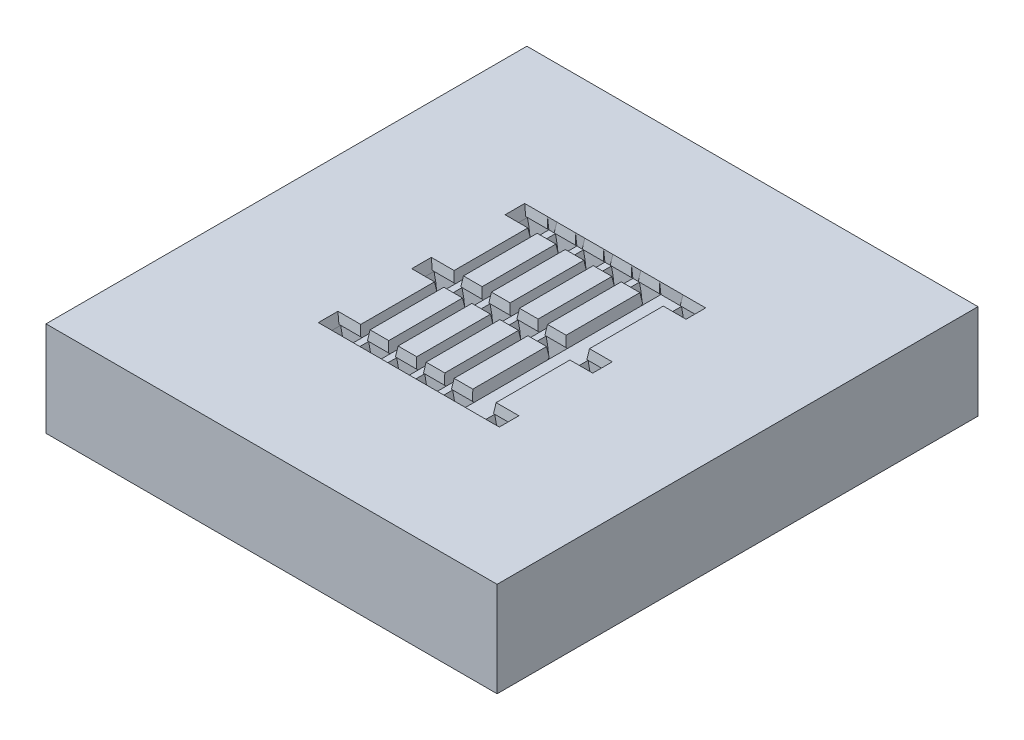
SolidWorks part; units mm, degrees
ref_plane "Front Plane" through (0, 0, 0) normal (0, 0, 1) x (1, 0, 0)
ref_plane "Top Plane" through (0, 0, 0) normal (0, 1, 0) x (1, 0, 0)
ref_plane "Right Plane" through (0, 0, 0) normal (1, 0, 0) x (0, 0, -1)
sketch "Sketch1" plane through (0, 0, 0) normal (0, 1, 0) x (1, 0, 0)
  line L0 (0, 0) -> (0, 25.75) construction
  line L1 (-24.1562, 25.75) -> (24.1562, 25.75)
  line L2 (-24.1562, 25.75) -> (-24.1562, -25.75)
  line L3 (-24.1562, -25.75) -> (24.1562, -25.75)
  line L4 (24.1562, 25.75) -> (24.1562, -25.75)
  line L5 (0, 0) -> (24.1562, 0) construction
  line L6 (24.1562, 25.75) -> (24.1562, -25.75) construction
  line L7 (-24.1562, 25.75) -> (24.1562, 25.75) construction
sketch "Sketch3" plane through (0, 0, 0) normal (1, 0, 0) x (0, 0, -1)
  line L0 (25.75, -12) -> (-25.75, -12) construction
  line L1 (25.75, 0) -> (-25.75, 0) construction
  line L2 (25.75, 0) -> (25.75, -12) construction
  line L3 (25.75, -12) -> (-25.75, -12)
  line L4 (-25.75, 0) -> (-25.75, -12) construction
  line L5 (25.75, -1.844) -> (11.05, -1.844)
  line L6 (-25.75, -1.844) -> (-25.75, -12)
  line L7 (25.75, -1.844) -> (25.75, -12)
  line L8 (1.05, -3) -> (0.9, -2.85) construction
  line L9 (0.9, -2.85) -> (1.05, -1.844) construction
  line L10 (1.05, -3) -> (1.05, -6.5) construction
  line L11 (-1.05, -3) -> (-0.9, -2.85) construction
  line L12 (-0.9, -2.85) -> (-1.05, -1.844) construction
  line L13 (-1.05, -3) -> (-1.05, -6.5) construction
  line L14 (1.05, -6.5) -> (-1.05, -6.5) construction
  line L15 (-8.95, -3) -> (-8.95, -6.5) construction
  line L16 (-8.95, -6.5) -> (-11.05, -6.5) construction
  line L17 (-11.05, -6.5) -> (-11.05, -3) construction
  line L18 (-10.9, -2.85) -> (-11.05, -1.844) construction
  line L19 (-9.1, -2.85) -> (-8.95, -1.844) construction
  line L20 (-11.05, -3) -> (-10.9, -2.85) construction
  line L21 (-8.95, -3) -> (-9.1, -2.85) construction
  line L22 (8.95, -6.5) -> (11.05, -6.5) construction
  line L23 (8.95, -3) -> (8.95, -6.5) construction
  line L24 (11.05, -6.5) -> (11.05, -3) construction
  line L25 (11.05, -3) -> (10.9, -2.85) construction
  line L26 (10.9, -2.85) -> (11.05, -1.844) construction
  line L27 (9.1, -2.85) -> (8.95, -1.844) construction
  line L28 (8.95, -3) -> (9.1, -2.85) construction
  line L29 (1.05, -3) -> (0.9, -2.85)
  line L30 (0.9, -2.85) -> (1.05, -1.844)
  line L31 (1.05, -3) -> (1.05, -6.5)
  line L32 (-1.05, -3) -> (-0.9, -2.85)
  line L33 (-0.9, -2.85) -> (-1.05, -1.844)
  line L34 (-1.05, -3) -> (-1.05, -6.5)
  line L35 (1.05, -6.5) -> (-1.05, -6.5)
  line L36 (-8.95, -3) -> (-8.95, -6.5)
  line L37 (-8.95, -6.5) -> (-11.05, -6.5)
  line L38 (-11.05, -6.5) -> (-11.05, -3)
  line L39 (-10.9, -2.85) -> (-11.05, -1.844)
  line L40 (-9.1, -2.85) -> (-8.95, -1.844)
  line L41 (-11.05, -3) -> (-10.9, -2.85)
  line L42 (-8.95, -3) -> (-9.1, -2.85)
  line L43 (8.95, -6.5) -> (11.05, -6.5)
  line L44 (8.95, -3) -> (8.95, -6.5)
  line L45 (11.05, -6.5) -> (11.05, -3)
  line L46 (11.05, -3) -> (10.9, -2.85)
  line L47 (10.9, -2.85) -> (11.05, -1.844)
  line L48 (9.1, -2.85) -> (8.95, -1.844)
  line L49 (8.95, -3) -> (9.1, -2.85)
  line L50 (8.95, -1.844) -> (1.05, -1.844)
  line L51 (-1.05, -1.844) -> (-8.95, -1.844)
  line L52 (-11.05, -1.844) -> (-25.75, -1.844)
sketch "Sketch5" plane through (0, 0, 0) normal (0, 0, 1) x (1, 0, 0)
  line L0 (-7.1005, -3) -> (-7.25, -1.844) construction
  line L1 (-7.25, -1.844) -> (-9.25, -1.844) construction
  line L2 (-9.25, -1.844) -> (-9.3995, -3) construction
  line L3 (-7.384, -6.5) -> (-9.116, -6.5) construction
  line L4 (-6.3995, -3) -> (-6.25, -1.844) construction
  line L5 (-6.25, -1.844) -> (-4.25, -1.844) construction
  line L6 (-4.25, -1.844) -> (-4.1005, -3) construction
  line L7 (-6.116, -6.5) -> (-4.384, -6.5) construction
  line L8 (-1.384, -6.5) -> (-3.116, -6.5) construction
  line L9 (-3.25, -1.844) -> (-3.3995, -3) construction
  line L10 (-1.25, -1.844) -> (-3.25, -1.844) construction
  line L11 (-1.1005, -3) -> (-1.25, -1.844) construction
  line L12 (-0.3995, -3) -> (-0.25, -1.844) construction
  line L13 (-0.116, -6.5) -> (1.616, -6.5) construction
  line L14 (1.75, -1.844) -> (1.8995, -3) construction
  line L15 (-0.25, -1.844) -> (1.75, -1.844) construction
  line L16 (4.75, -1.844) -> (2.75, -1.844) construction
  line L17 (2.75, -1.844) -> (2.6005, -3) construction
  line L18 (4.8995, -3) -> (4.75, -1.844) construction
  line L19 (4.616, -6.5) -> (2.884, -6.5) construction
  line L20 (7.384, -6.5) -> (9.116, -6.5) construction
  line L21 (7.1005, -3) -> (7.25, -1.844) construction
  line L22 (9.25, -1.844) -> (9.3995, -3) construction
  line L23 (7.25, -1.844) -> (9.25, -1.844) construction
  line L24 (-7.1005, -3) -> (-7.25, -1.844)
  line L25 (-7.25, -1.844) -> (-9.25, -1.844)
  line L26 (-9.25, -1.844) -> (-9.3995, -3)
  line L27 (-7.384, -6.5) -> (-9.116, -6.5)
  line L28 (-6.3995, -3) -> (-6.25, -1.844)
  line L29 (-6.25, -1.844) -> (-4.25, -1.844)
  line L30 (-4.25, -1.844) -> (-4.1005, -3)
  line L31 (-6.116, -6.5) -> (-4.384, -6.5)
  line L32 (-1.384, -6.5) -> (-3.116, -6.5)
  line L33 (-3.25, -1.844) -> (-3.3995, -3)
  line L34 (-1.25, -1.844) -> (-3.25, -1.844)
  line L35 (-1.1005, -3) -> (-1.25, -1.844)
  line L36 (-0.3995, -3) -> (-0.25, -1.844)
  line L37 (-0.116, -6.5) -> (1.616, -6.5)
  line L38 (1.75, -1.844) -> (1.8995, -3)
  line L39 (-0.25, -1.844) -> (1.75, -1.844)
  line L40 (4.75, -1.844) -> (2.75, -1.844)
  line L41 (2.75, -1.844) -> (2.6005, -3)
  line L42 (4.8995, -3) -> (4.75, -1.844)
  line L43 (4.616, -6.5) -> (2.884, -6.5)
  line L44 (7.384, -6.5) -> (9.116, -6.5)
  line L45 (7.1005, -3) -> (7.25, -1.844)
  line L46 (9.25, -1.844) -> (9.3995, -3)
  line L47 (7.25, -1.844) -> (9.25, -1.844)
  arc A0 (-9.116, -6.5) -> (-9.3995, -3) centre (-19.7262, -5.5981) ccw construction
  arc A1 (-7.1005, -3) -> (-7.384, -6.5) centre (3.2262, -5.5981) ccw construction
  arc A2 (-6.116, -6.5) -> (-6.3995, -3) centre (-16.7262, -5.5981) ccw construction
  arc A3 (-4.1005, -3) -> (-4.384, -6.5) centre (6.2262, -5.5981) ccw construction
  arc A4 (-3.116, -6.5) -> (-3.3995, -3) centre (-13.7262, -5.5981) ccw construction
  arc A5 (-1.1005, -3) -> (-1.384, -6.5) centre (9.2262, -5.5981) ccw construction
  arc A6 (-0.116, -6.5) -> (-0.3995, -3) centre (-10.7262, -5.5981) ccw construction
  arc A7 (1.8995, -3) -> (1.616, -6.5) centre (12.2262, -5.5981) ccw construction
  arc A8 (4.8995, -3) -> (4.616, -6.5) centre (15.2262, -5.5981) ccw construction
  arc A9 (2.884, -6.5) -> (2.6005, -3) centre (-7.7262, -5.5981) ccw construction
  arc A10 (7.384, -6.5) -> (7.1005, -3) centre (-3.2262, -5.5981) ccw construction
  arc A11 (9.3995, -3) -> (9.116, -6.5) centre (19.7262, -5.5981) ccw construction
  arc A12 (-9.116, -6.5) -> (-9.3995, -3) centre (-19.7262, -5.5981) ccw
  arc A13 (-7.1005, -3) -> (-7.384, -6.5) centre (3.2262, -5.5981) ccw
  arc A14 (-6.116, -6.5) -> (-6.3995, -3) centre (-16.7262, -5.5981) ccw
  arc A15 (-4.1005, -3) -> (-4.384, -6.5) centre (6.2262, -5.5981) ccw
  arc A16 (-3.116, -6.5) -> (-3.3995, -3) centre (-13.7262, -5.5981) ccw
  arc A17 (-1.1005, -3) -> (-1.384, -6.5) centre (9.2262, -5.5981) ccw
  arc A18 (-0.116, -6.5) -> (-0.3995, -3) centre (-10.7262, -5.5981) ccw
  arc A19 (1.8995, -3) -> (1.616, -6.5) centre (12.2262, -5.5981) ccw
  arc A20 (4.8995, -3) -> (4.616, -6.5) centre (15.2262, -5.5981) ccw
  arc A21 (2.884, -6.5) -> (2.6005, -3) centre (-7.7262, -5.5981) ccw
  arc A22 (7.384, -6.5) -> (7.1005, -3) centre (-3.2262, -5.5981) ccw
  arc A23 (9.3995, -3) -> (9.116, -6.5) centre (19.7262, -5.5981) ccw
extrude "Boss-Extrude2" add sketch "Sketch1" against normal up to vertex (12 mm away) from vertex at -1.844 starting at point (0, -1.844, 25.75)
sketch "Sketch6" plane through (0, 0, 0) normal (0, 0, 1) x (1, 0, 0)
  line L0 (-9.3995, -3) -> (-9.6904, -1.844)
  line L1 (-9.6904, -1.844) -> (9.6904, -1.844)
  line L2 (9.6904, -1.844) -> (9.3995, -3)
  line L3 (-7.25, -1.844) -> (-9.25, -1.844) construction
  line L4 (-9.116, -6.5) -> (9.116, -6.5)
  line L5 (-9.6904, -1.844) -> (-9.6904, -6.5) construction
  line L6 (-9.6904, -6.5) -> (-9.116, -6.5) construction
  line L7 (9.6904, -1.844) -> (9.6904, -6.5) construction
  line L8 (9.6904, -6.5) -> (9.116, -6.5) construction
  arc A0 (9.3995, -3) -> (9.116, -6.5) centre (19.7262, -5.5981) ccw construction
  arc A1 (-9.116, -6.5) -> (-9.3995, -3) centre (-19.7262, -5.5981) ccw construction
  arc A2 (-9.116, -6.5) -> (-9.3995, -3) centre (-19.7262, -5.5981) ccw
  arc A3 (9.3995, -3) -> (9.116, -6.5) centre (19.7262, -5.5981) ccw
sketch "Sketch7" plane through (0, 0, 0) normal (1, 0, 0) x (0, 0, -1)
  line L0 (10.9, -2.85) -> (11.05, -1.844) construction
  line L1 (-10.9, -2.85) -> (-11.05, -1.844) construction
  line L2 (-11.05, -3) -> (-10.9, -2.85) construction
  line L3 (-11.05, -6.5) -> (-11.05, -3) construction
  line L4 (-8.95, -6.5) -> (-11.05, -6.5) construction
  line L5 (-8.95, -3) -> (-8.95, -6.5) construction
  line L6 (-8.95, -3) -> (-9.1, -2.85) construction
  line L7 (-9.1, -2.85) -> (-8.95, -1.844) construction
  line L8 (-0.9, -2.85) -> (-1.05, -1.844) construction
  line L9 (-1.05, -3) -> (-0.9, -2.85) construction
  line L10 (-1.05, -3) -> (-1.05, -6.5) construction
  line L11 (1.05, -6.5) -> (-1.05, -6.5) construction
  line L12 (1.05, -3) -> (1.05, -6.5) construction
  line L13 (1.05, -3) -> (0.9, -2.85) construction
  line L14 (0.9, -2.85) -> (1.05, -1.844) construction
  line L15 (9.1, -2.85) -> (8.95, -1.844) construction
  line L16 (8.95, -3) -> (9.1, -2.85) construction
  line L17 (8.95, -3) -> (8.95, -6.5) construction
  line L18 (8.95, -6.5) -> (11.05, -6.5) construction
  line L19 (11.05, -6.5) -> (11.05, -3) construction
  line L20 (11.05, -3) -> (10.9, -2.85) construction
  line L21 (10.9, -2.85) -> (11.05, -1.844)
  line L22 (-10.9, -2.85) -> (-11.05, -1.844)
  line L23 (-11.05, -3) -> (-10.9, -2.85)
  line L24 (-11.05, -6.5) -> (-11.05, -3)
  line L25 (-8.95, -6.5) -> (-11.05, -6.5)
  line L26 (-8.95, -3) -> (-8.95, -6.5)
  line L27 (-8.95, -3) -> (-9.1, -2.85)
  line L28 (-9.1, -2.85) -> (-8.95, -1.844)
  line L29 (-0.9, -2.85) -> (-1.05, -1.844)
  line L30 (-1.05, -3) -> (-0.9, -2.85)
  line L31 (-1.05, -3) -> (-1.05, -6.5)
  line L32 (1.05, -6.5) -> (-1.05, -6.5)
  line L33 (1.05, -3) -> (1.05, -6.5)
  line L34 (1.05, -3) -> (0.9, -2.85)
  line L35 (0.9, -2.85) -> (1.05, -1.844)
  line L36 (9.1, -2.85) -> (8.95, -1.844)
  line L37 (8.95, -3) -> (9.1, -2.85)
  line L38 (8.95, -3) -> (8.95, -6.5)
  line L39 (8.95, -6.5) -> (11.05, -6.5)
  line L40 (11.05, -6.5) -> (11.05, -3)
  line L41 (11.05, -3) -> (10.9, -2.85)
  line L42 (11.05, -1.844) -> (8.95, -1.844)
  line L43 (1.05, -1.844) -> (-1.05, -1.844)
  line L44 (-8.95, -1.844) -> (-11.05, -1.844)
extrude "Cut-Extrude1" cut sketch "Sketch7" along normal up to vertex (9.6904 mm away) from vertex at -9.6904 starting at point (-9.6904, -1.844, 0)
sketch "Sketch8" plane through (0, 0, 0) normal (0, 0, 1) x (1, 0, 0)
  line L0 (-7.25, -1.844) -> (-7.1005, -3)
  line L1 (-7.1005, -3) -> (-6.3995, -3)
  line L2 (-6.3995, -3) -> (-6.25, -1.844)
  line L3 (-6.25, -1.844) -> (-7.25, -1.844)
  line L4 (-4.25, -1.844) -> (-4.1005, -3)
  line L5 (-4.1005, -3) -> (-3.3995, -3)
  line L6 (-3.3995, -3) -> (-3.25, -1.844)
  line L7 (-3.25, -1.844) -> (-4.25, -1.844)
  line L8 (-1.25, -1.844) -> (-1.1005, -3)
  line L9 (-1.1005, -3) -> (-0.3995, -3)
  line L10 (-0.3995, -3) -> (-0.25, -1.844)
  line L11 (-0.25, -1.844) -> (-1.25, -1.844)
  line L12 (1.8995, -3) -> (2.6005, -3)
  line L13 (2.6005, -3) -> (2.75, -1.844)
  line L14 (2.75, -1.844) -> (1.75, -1.844)
  line L15 (1.75, -1.844) -> (1.8995, -3)
  line L16 (4.8995, -3) -> (7.1005, -3)
  line L17 (7.1005, -3) -> (7.25, -1.844)
  line L18 (7.25, -1.844) -> (4.75, -1.844)
  line L19 (4.75, -1.844) -> (4.8995, -3)
extrude "Cut-Extrude2" cut sketch "Sketch8" against normal up to vertex (11.05 mm away) from vertex at 11.05 starting at point (0, -1.844, 11.05)
sketch "Sketch9" plane through (0, 0, 0) normal (0, 0, 1) x (1, 0, 0)
  line L0 (-9.6904, -1.844) -> (-9.6904, -6.5) construction
  line L1 (-9.3995, -3) -> (-9.6904, -1.844) construction
  line L2 (-9.6904, -6.5) -> (-9.116, -6.5) construction
  line L3 (9.6904, -1.844) -> (9.3995, -3) construction
  line L4 (9.6904, -1.844) -> (9.6904, -6.5) construction
  line L5 (9.6904, -6.5) -> (9.116, -6.5) construction
  line L6 (-9.6904, -1.844) -> (-9.6904, -6.5)
  line L7 (-9.3995, -3) -> (-9.6904, -1.844)
  line L8 (-9.6904, -6.5) -> (-9.116, -6.5)
  line L9 (9.6904, -1.844) -> (9.3995, -3)
  line L10 (9.6904, -1.844) -> (9.6904, -6.5)
  line L11 (9.6904, -6.5) -> (9.116, -6.5)
  line L12 (-7.1005, -3) -> (-6.3995, -3)
  line L13 (-4.1005, -3) -> (-3.3995, -3)
  line L14 (-1.1005, -3) -> (-0.3995, -3)
  line L15 (1.8995, -3) -> (2.6005, -3)
  line L16 (2.884, -6.5) -> (1.616, -6.5)
  line L17 (-0.116, -6.5) -> (-1.384, -6.5)
  line L18 (-3.116, -6.5) -> (-4.384, -6.5)
  line L19 (-6.116, -6.5) -> (-7.384, -6.5)
  line L20 (4.8995, -3) -> (7.1005, -3)
  line L21 (7.384, -6.5) -> (4.616, -6.5)
  arc A0 (-9.116, -6.5) -> (-9.3995, -3) centre (-19.7262, -5.5981) ccw construction
  arc A1 (-7.1005, -3) -> (-7.384, -6.5) centre (3.2262, -5.5981) ccw construction
  arc A2 (-6.116, -6.5) -> (-6.3995, -3) centre (-16.7262, -5.5981) ccw construction
  arc A3 (-4.1005, -3) -> (-4.384, -6.5) centre (6.2262, -5.5981) ccw construction
  arc A4 (-3.116, -6.5) -> (-3.3995, -3) centre (-13.7262, -5.5981) ccw construction
  arc A5 (-1.1005, -3) -> (-1.384, -6.5) centre (9.2262, -5.5981) ccw construction
  arc A6 (-0.116, -6.5) -> (-0.3995, -3) centre (-10.7262, -5.5981) ccw construction
  arc A7 (1.8995, -3) -> (1.616, -6.5) centre (12.2262, -5.5981) ccw construction
  arc A8 (2.884, -6.5) -> (2.6005, -3) centre (-7.7262, -5.5981) ccw construction
  arc A9 (4.8995, -3) -> (4.616, -6.5) centre (15.2262, -5.5981) ccw construction
  arc A10 (7.384, -6.5) -> (7.1005, -3) centre (-3.2262, -5.5981) ccw construction
  arc A11 (9.3995, -3) -> (9.116, -6.5) centre (19.7262, -5.5981) ccw construction
  arc A12 (-9.116, -6.5) -> (-9.3995, -3) centre (-19.7262, -5.5981) ccw
  arc A13 (-7.1005, -3) -> (-7.384, -6.5) centre (3.2262, -5.5981) ccw
  arc A14 (-6.116, -6.5) -> (-6.3995, -3) centre (-16.7262, -5.5981) ccw
  arc A15 (-4.1005, -3) -> (-4.384, -6.5) centre (6.2262, -5.5981) ccw
  arc A16 (-3.116, -6.5) -> (-3.3995, -3) centre (-13.7262, -5.5981) ccw
  arc A17 (-1.1005, -3) -> (-1.384, -6.5) centre (9.2262, -5.5981) ccw
  arc A18 (-0.116, -6.5) -> (-0.3995, -3) centre (-10.7262, -5.5981) ccw
  arc A19 (1.8995, -3) -> (1.616, -6.5) centre (12.2262, -5.5981) ccw
  arc A20 (2.884, -6.5) -> (2.6005, -3) centre (-7.7262, -5.5981) ccw
  arc A21 (4.8995, -3) -> (4.616, -6.5) centre (15.2262, -5.5981) ccw
  arc A22 (7.384, -6.5) -> (7.1005, -3) centre (-3.2262, -5.5981) ccw
  arc A23 (9.3995, -3) -> (9.116, -6.5) centre (19.7262, -5.5981) ccw
extrude "Boss-Extrude3" add sketch "Sketch9" along normal up to vertex (11.05 mm away) from vertex at -11.05 starting at point (0, -6.5, -11.05)
